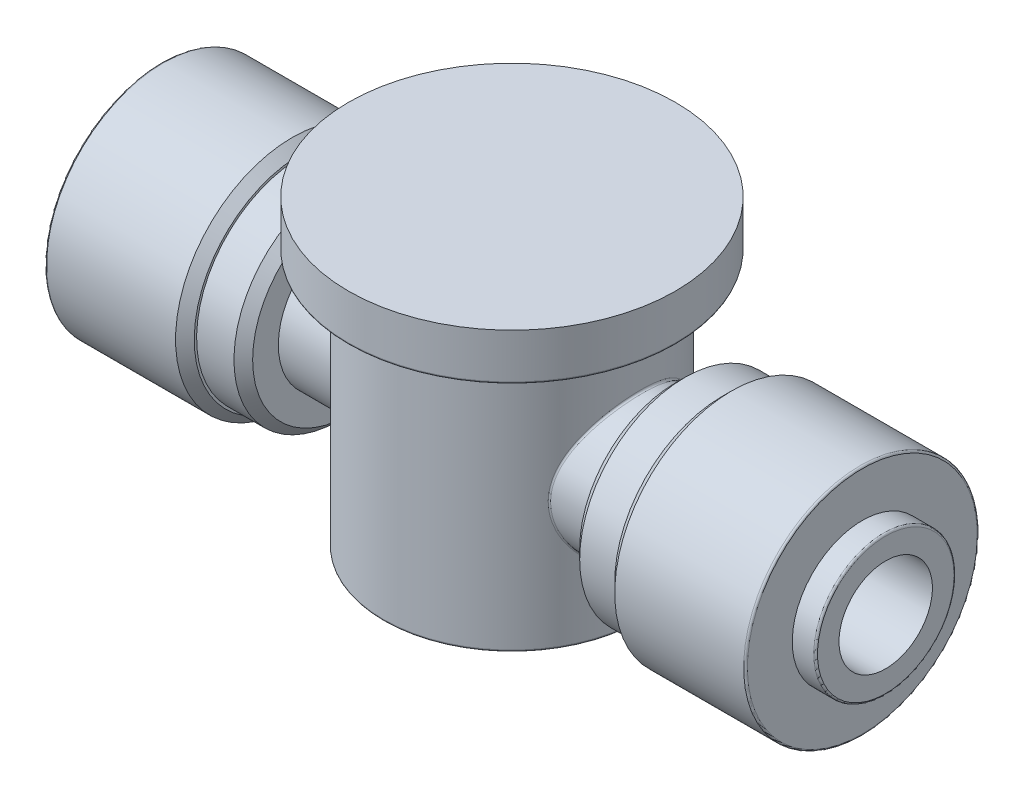
SolidWorks part; units mm, degrees
ref_plane "Front Plane" through (0, 0, 0) normal (0, 0, 1) x (1, 0, 0)
ref_plane "Top Plane" through (0, 0, 0) normal (0, 1, 0) x (1, 0, 0)
ref_plane "Right Plane" through (0, 0, 0) normal (1, 0, 0) x (0, 0, -1)
sketch "Sketch1" plane through (0, 0, 0) normal (0, 1, 0) x (1, 0, 0)
  circle A0 centre (0, 0) radius 8.7312
  dimension "D1" = 17.4625
extrude "Boss-Extrude1" add sketch "Sketch1" along normal mid plane 17.4625
sketch "Sketch2" plane through (0, 0, 0) normal (1, 0, 0) x (0, 0, -1)
  circle A0 centre (0, 0) radius 4.7625
  dimension "D1" = 9.525
extrude "Boss-Extrude2" add sketch "Sketch2" along normal mid plane 50.8
sketch "Sketch3" plane through (0, 0, 0) normal (0, 0, 1) x (1, 0, 0)
  line L0 (0, 0) -> (25.4, 0) construction
  line L1 (25.4, -4.7625) -> (25.4, 4.7625) construction
  line L2 (23.8125, 0) -> (23.8125, 7.9375)
  line L3 (23.8125, 7.9375) -> (14.2875, 7.9375)
  line L4 (14.2875, 7.9375) -> (14.2875, 7.1437)
  line L5 (14.2875, 7.1437) -> (11.1125, 7.1437)
  line L8 (11.1125, 7.1437) -> (11.1125, 0)
  line L9 (11.1125, 0) -> (23.8125, 0)
  dimension "D1" = 1.5875
  dimension "D2" = 9.525
  dimension "D3" = 12.7
  dimension "D4" = 15.875
  dimension "D5" = 14.2875
revolve "Revolve1" add sketch "Sketch3" angle 360 about L0
mirror "Mirror1" about plane through (0, 0, 0) normal (1, 0, 0) of "Revolve1"
sketch "Sketch4" plane through (0, 8.7312, 0) normal (0, 1, 0) x (1, 0, 0)
  circle A0 centre (0, 0) radius 11.1125
  dimension "D1" = 22.225
extrude "Boss-Extrude5" add sketch "Sketch4" along normal blind 3.175
fillet "Fillet1" radius 0.127 8 edges at (0, 8.7312, 11.1125) (0, -8.7312, 8.7312) (-23.8125, -7.9375, 0) (-25.4, 0, -4.7625) (23.8125, -7.9375, 0) (25.4, 0, -4.7625) (-7.3298, -0.4148, -4.7444) (7.3298, 0.4148, -4.7444)
chamfer "Chamfer1" distance 0.635 angle 45 4 edges at (-14.2875, -7.9375, 0) (11.1125, -7.1438, 0) (14.2875, -7.9375, 0) (-11.1125, -7.1438, 0)
sketch "Sketch5" plane through (-25.4, 0, 0) normal (-1, 0, 0) x (0, 0, 1)
  circle A0 centre (0, 0) radius 3.175
  dimension "D1" = 6.35
extrude "Cut-Extrude1" cut sketch "Sketch5" against normal through all
